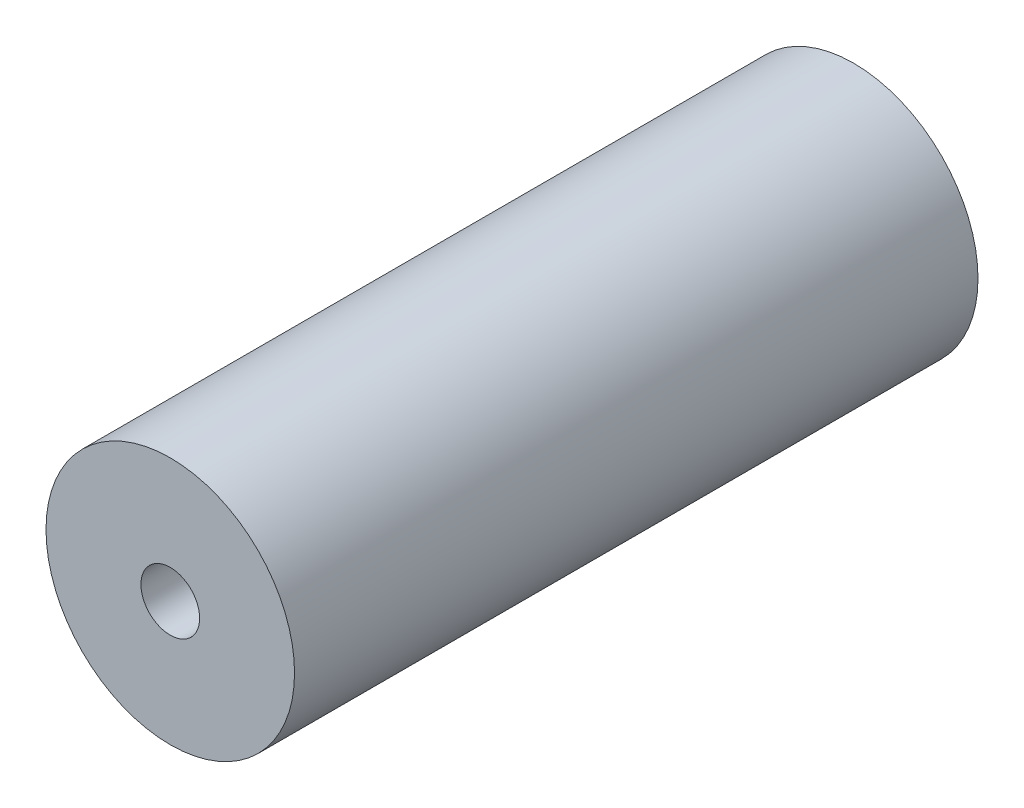
SolidWorks part; units mm, degrees
ref_plane "Front Plane" through (0, 0, 0) normal (0, 0, 1) x (1, 0, 0)
ref_plane "Top Plane" through (0, 0, 0) normal (0, 1, 0) x (1, 0, 0)
ref_plane "Right Plane" through (0, 0, 0) normal (1, 0, 0) x (0, 0, -1)
sketch "Sketch1" plane through (0, 0, 0) normal (0, 0, 1) x (1, 0, 0)
  circle A0 centre (0, 0) radius 12.7
  dimension "D1" = 25.4
extrude "Boss-Extrude1" add sketch "Sketch1" along normal blind 69.85
sketch "Sketch2" plane through (0, 0, 69.85) normal (0, 0, 1) x (1, 0, 0)
  circle A0 centre (0, 0) radius 3
  dimension "D1" = 6
extrude "Cut-Extrude3" cut sketch "Sketch2" against normal up to surface (69.85 mm away) up to face at (12.7, 0, 0)
